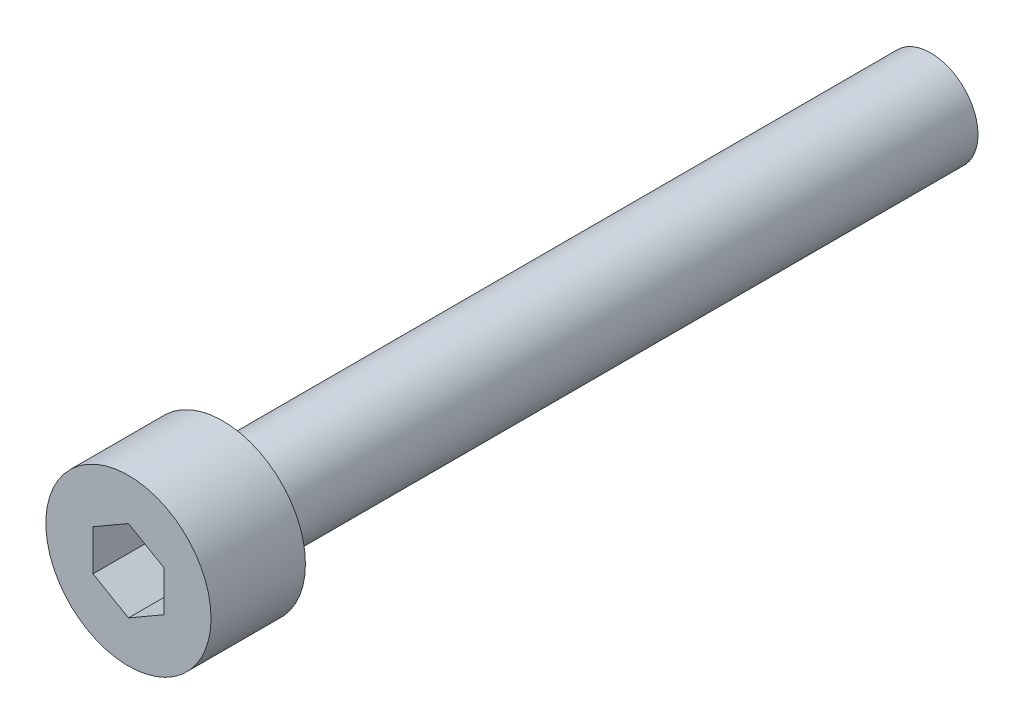
SolidWorks part; units mm, degrees
ref_plane "前视基准面" through (0, 0, 0) normal (0, 0, 1) x (1, 0, 0)
ref_plane "上视基准面" through (0, 0, 0) normal (0, 1, 0) x (1, 0, 0)
ref_plane "右视基准面" through (0, 0, 0) normal (1, 0, 0) x (0, 0, -1)
other "Configuration Table"
sketch "Profile_1" plane through (0, 0, 0) normal (0, 0, 1) x (1, 0, 0)
  circle A0 centre (0, 0) radius 2
extrude "Thread_envelope" add sketch "Profile_1" along normal blind 30 from offset 30
sketch "Profile_2" plane through (0, 0, 0) normal (0, 0, 1) x (1, 0, 0)
  line L0 (1.5, 0.866) -> (0, 1.7321)
  line L1 (0, 1.7321) -> (-1.5, 0.866)
  line L2 (-1.5, 0.866) -> (-1.5, -0.866)
  line L3 (-1.5, -0.866) -> (0, -1.7321)
  line L4 (0, -1.7321) -> (1.5, -0.866)
  line L5 (1.5, -0.866) -> (1.5, 0.866)
  circle A0 centre (0, 0) radius 3.5
extrude "Socket_head" add sketch "Profile_2" along normal blind 4 from offset 0
